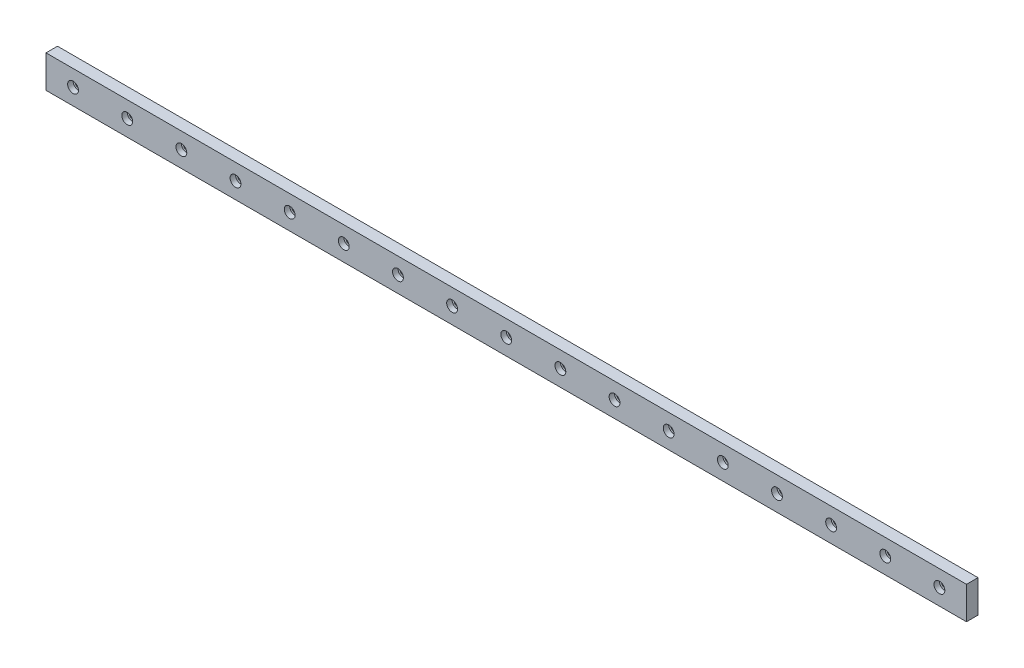
SolidWorks part; units mm, degrees
material "SKD11淬火HRC56-60"
ref_plane "前基準面" through (0, 0, 0) normal (0, 0, 1) x (1, 0, 0)
ref_plane "上基準面" through (0, 0, 0) normal (0, 1, 0) x (1, 0, 0)
ref_plane "右基準面" through (0, 0, 0) normal (1, 0, 0) x (0, 0, -1)
sketch "草图1" plane through (0, 0, 0) normal (0, 0, 1) x (1, 0, 0)
  line L1 (0, 0) -> (680, 0)
  line L2 (0, 0) -> (0, 24)
  line L3 (0, 24) -> (680, 24)
  line L4 (680, 0) -> (680, 24)
  dimension "D1" = 24
  dimension "D2" = 680
extrude "凸台-拉伸1" add sketch "草图1" along normal blind 8.5
hole_wizard "M4 六角凹头螺钉的柱形沉头孔1" positions "草图3" profile "草图2" counterbore size "M4" standard "ISO" end condition through all
sketch "草图3" plane through (0, 0, 8.5) normal (0, 0, 1) x (1, 0, 0)
  line L0 (0, 12) -> (63.3284, 12) construction
  line L1 (0, 24) -> (0, 0) construction
  point P1 (20, 12)
  dimension "D1" = 20
sketch "草图2" plane through (20, 12, 8.5) normal (1, 0, 0) x (0, -1, 0)
  line L0 (0, 0) -> (0, 8.5)
  line L1 (0, 8.5) -> (2.4, 8.5)
  line L3 (2.4, 8.5) -> (2.4, 4)
  line L4 (2.4, 4) -> (4, 4)
  line L5 (4, 4) -> (4, 0)
  line L7 (4, 0) -> (0, 0)
  line L11 (0, -6.35) -> (0, 107.95) construction
  dimension "通孔孔直径" = 4.8
  dimension "通孔孔深度" = 8.5
  dimension "柱形沉头孔直径" = 8
  dimension "柱形沉头孔深度" = 4
pattern_linear "阵列(线性)1" count 17 spacing 40 along (1, 0, 0) of "M4 六角凹头螺钉的柱形沉头孔1"
